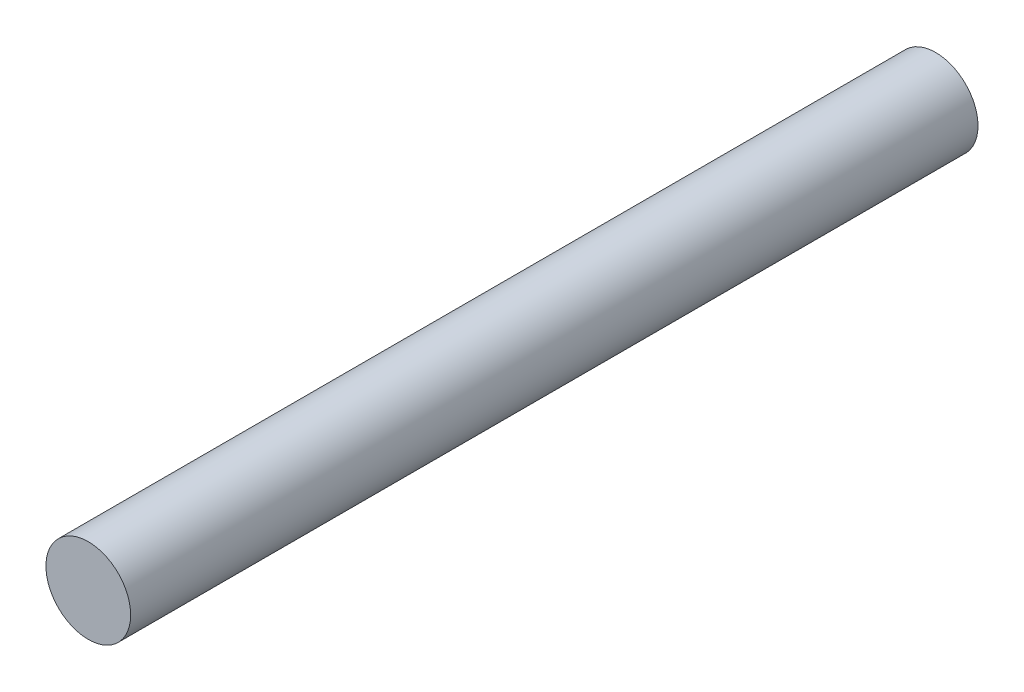
SolidWorks part; units mm, degrees
ref_plane "Front" through (0, 0, 0) normal (0, 0, 1) x (1, 0, 0)
ref_plane "Top" through (0, 0, 0) normal (0, 1, 0) x (1, 0, 0)
ref_plane "Right" through (0, 0, 0) normal (1, 0, 0) x (0, 0, -1)
sketch "Sketch1" plane through (0, 0, 0) normal (0, 0, 1) x (1, 0, 0)
  circle A0 centre (0, 0) radius 1.5
  dimension "D1" = 3
extrude "Boss-Extrude1" add sketch "Sketch1" along normal mid plane 30
